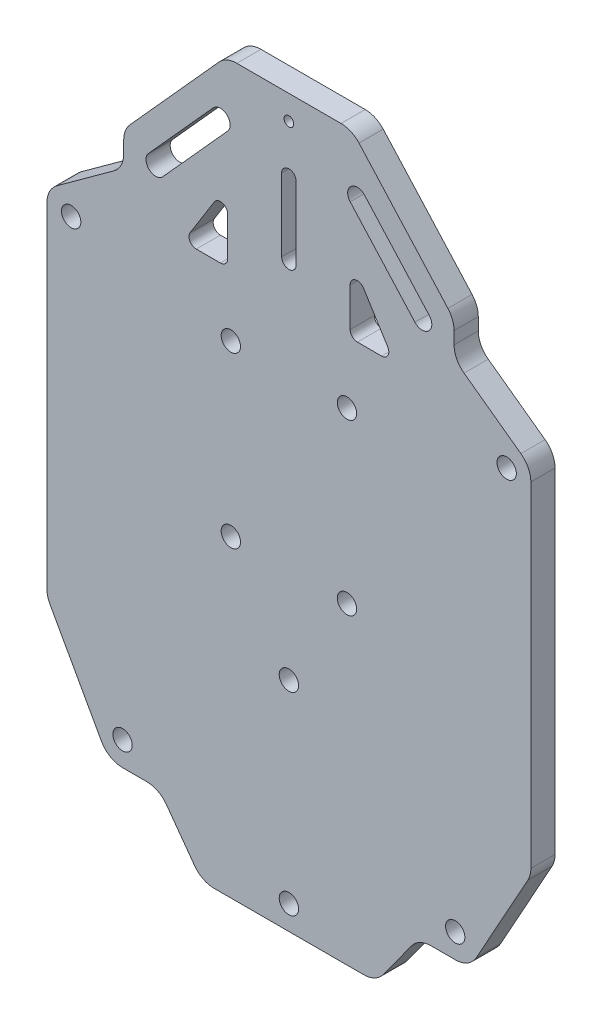
SolidWorks part; units mm, degrees
material "Acrylic (Medium-high impact)"
ref_plane "Front Plane" through (0, 0, 0) normal (0, 0, 1) x (1, 0, 0)
ref_plane "Top Plane" through (0, 0, 0) normal (0, 1, 0) x (1, 0, 0)
ref_plane "Right Plane" through (0, 0, 0) normal (1, 0, 0) x (0, 0, -1)
sketch "Sketch2" plane through (0, 0, 0) normal (0, 0, 1) x (1, 0, 0)
  line L0 (0, 0) -> (0, -150) construction
  line L1 (10.7739, 0) -> (-10.7739, 0)
  line L2 (-14.4896, -1.6543) -> (-32.8523, -22.0482)
  line L3 (-34.1366, -25.3939) -> (-34.1366, -27.9269)
  line L4 (-36.1977, -31.972) -> (-47.9389, -40.5025)
  line L5 (-50, -44.5476) -> (-50, -113.7061)
  line L6 (-19.4975, -147.9389) -> (-25.3193, -139.9258)
  line L7 (-29.3644, -137.8647) -> (-34.3726, -137.8647)
  line L8 (-38.7449, -135.2901) -> (-49.3724, -116.1315)
  line L9 (-15.4524, -150) -> (15.4524, -150)
  line L10 (19.4975, -147.9389) -> (25.3193, -139.9258)
  line L11 (29.3644, -137.8647) -> (34.3726, -137.8647)
  line L12 (38.7449, -135.2901) -> (49.3724, -116.1315)
  line L13 (50, -44.5476) -> (50, -113.7061)
  line L14 (36.1977, -31.972) -> (47.9389, -40.5025)
  line L15 (34.1366, -25.3939) -> (34.1366, -27.9269)
  line L16 (14.4896, -1.6543) -> (32.8523, -22.0482)
  line L17 (-14.147, -11.7352) -> (-27.5296, -26.5981) construction
  line L18 (-12.6607, -13.0735) -> (-26.0433, -27.9364)
  line L19 (-15.6333, -10.397) -> (-29.0159, -25.2599)
  line L20 (14.147, -37.4364) -> (19.147, -37.4364)
  line L21 (-14.147, -37.4364) -> (-19.147, -37.4364)
  line L22 (-12.647, -27.9364) -> (-12.647, -35.9364)
  line L24 (20.419, -35.1414) -> (15.419, -27.1414)
  line L26 (-20.419, -35.1414) -> (-15.419, -27.1414)
  line L27 (12.647, -27.9364) -> (12.647, -35.9364)
  line L28 (14.147, -11.7352) -> (27.5296, -26.5981) construction
  line L29 (12.6607, -13.0735) -> (26.0433, -27.9364)
  line L30 (15.6333, -10.397) -> (29.0159, -25.2599)
  line L31 (0, -15) -> (0, -30) construction
  line L32 (1.5, -15) -> (1.5, -30)
  line L33 (-1.5, -15) -> (-1.5, -30)
  line L34 (0, -50.308) -> (-12, -50.308) construction
  line L35 (14.147, -123.5201) -> (-14.147, -123.5201) construction
  arc A0 (-50, -113.7061) -> (-49.3724, -116.1315) centre (-45, -113.7061) ccw
  arc A1 (-19.4975, -147.9389) -> (-15.4524, -150) centre (-15.4524, -145) ccw
  arc A2 (-25.3193, -139.9258) -> (-29.3644, -137.8647) centre (-29.3644, -142.8647) ccw
  arc A3 (-34.3726, -137.8647) -> (-38.7449, -135.2901) centre (-34.3726, -132.8647) cw
  arc A4 (-47.9389, -40.5025) -> (-50, -44.5476) centre (-45, -44.5476) ccw
  arc A5 (-34.1366, -27.9269) -> (-36.1977, -31.972) centre (-39.1366, -27.9269) cw
  arc A6 (-32.8523, -22.0482) -> (-34.1366, -25.3939) centre (-29.1366, -25.3939) ccw
  arc A7 (-10.7739, 0) -> (-14.4896, -1.6543) centre (-10.7739, -5) ccw
  arc A8 (19.4975, -147.9389) -> (15.4524, -150) centre (15.4524, -145) cw
  arc A9 (25.3193, -139.9258) -> (29.3644, -137.8647) centre (29.3644, -142.8647) cw
  arc A10 (34.3726, -137.8647) -> (38.7449, -135.2901) centre (34.3726, -132.8647) ccw
  arc A11 (50, -113.7061) -> (49.3724, -116.1315) centre (45, -113.7061) cw
  arc A12 (47.9389, -40.5025) -> (50, -44.5476) centre (45, -44.5476) cw
  arc A13 (34.1366, -27.9269) -> (36.1977, -31.972) centre (39.1366, -27.9269) ccw
  arc A14 (32.8523, -22.0482) -> (34.1366, -25.3939) centre (29.1366, -25.3939) cw
  arc A15 (10.7739, 0) -> (14.4896, -1.6543) centre (10.7739, -5) cw
  arc A16 (-12.6607, -13.0735) -> (-15.6333, -10.397) centre (-14.147, -11.7352) ccw
  arc A17 (-29.0159, -25.2599) -> (-26.0433, -27.9364) centre (-27.5296, -26.5981) ccw
  circle A18 centre (0, -5) radius 1
  arc A19 (-12.647, -27.9364) -> (-15.419, -27.1414) centre (-14.147, -27.9364) ccw
  arc A20 (-14.147, -37.4364) -> (-12.647, -35.9364) centre (-14.147, -35.9364) ccw
  arc A21 (-14.147, -37.4364) -> (-12.647, -35.9364) centre (-14.147, -35.9364) ccw
  arc A22 (-20.419, -35.1414) -> (-19.147, -37.4364) centre (-19.147, -35.9364) ccw
  arc A23 (20.419, -35.1414) -> (19.147, -37.4364) centre (19.147, -35.9364) cw
  arc A24 (12.647, -27.9364) -> (15.419, -27.1414) centre (14.147, -27.9364) cw
  arc A25 (14.147, -37.4364) -> (12.647, -35.9364) centre (14.147, -35.9364) cw
  arc A26 (12.6607, -13.0735) -> (15.6333, -10.397) centre (14.147, -11.7352) cw
  arc A27 (29.0159, -25.2599) -> (26.0433, -27.9364) centre (27.5296, -26.5981) cw
  arc A28 (1.5, -15) -> (-1.5, -15) centre (0, -15) ccw
  arc A29 (-1.5, -30) -> (1.5, -30) centre (0, -30) ccw
  circle A30 centre (0, -145) radius 2
  circle A31 centre (0, -105) radius 2
  circle A32 centre (-12, -50.308) radius 2
  circle A33 centre (12, -50.308) radius 2
  circle A34 centre (12, -85.308) radius 2
  circle A35 centre (-12, -85.308) radius 2
  circle A36 centre (-34.3726, -132.8647) radius 2
  circle A37 centre (34.3726, -132.8647) radius 2
  circle A38 centre (-45, -44.5476) radius 2
  circle A39 centre (45, -44.5476) radius 2
  text T0 "OCOBOT" font "Exotc350 Bd BT" height 4
  point P13 (-50, -115)
  point P16 (-18, -150)
  point P19 (-26.8168, -137.8647)
  point P22 (-37.3168, -137.8647)
  point P25 (-50, -42)
  point P28 (-34.1366, -30.4746)
  point P31 (-34.1366, -23.4746)
  point P34 (-13, 0)
  point P56 (34.1366, -23.4746)
  point P62 (-20.8383, -19.1667)
  point P71 (-18.0805, -35.9364)
  point P73 (-14.147, -31.9364)
  point P76 (0, -22.5)
  point P100 (20.8383, -19.1667)
  point P111 (0, -75)
  point P125 (0, -123.5201)
  dimension "D10" = 5
  dimension "D13" = 5
  dimension "D14" = 5
  dimension "D16" = 2
  dimension "D19" = 2
  dimension "D20" = 5
  dimension "D24" = 1.5
  dimension "D25" = 1.5
  dimension "D26" = 1.5
  dimension "D34" = 1.5
  dimension "D37" = 4
  dimension "D38" = 4
  dimension "D40" = 4
  dimension "D47" = 4
  dimension "D48" = 4
  dimension "D49" = 5
  dimension "D50" = 4
  dimension "D51" = 4
  dimension "D52" = 4
  dimension "D53" = 4
  dimension "D1" = 150
  dimension "D2" = 100
  dimension "D3" = 73
  dimension "D4" = 36
  dimension "D5" = 15
  dimension "D6" = 26
  dimension "D7" = 35
  dimension "D8" = 10.5
  dimension "D9" = 54
  dimension "D11" = 48
  dimension "D12" = 7
  dimension "D15" = 5
  dimension "D17" = 14.147
  dimension "D18" = 20
  dimension "D21" = 8
  dimension "D22" = 5
  dimension "D23" = 14.147
  dimension "D27" = 19.478
  dimension "D28" = 112.5636
  dimension "D29" = 31.9364
  dimension "D30" = 27.9364
  dimension "D31" = 14.147
  dimension "D32" = 18.0805
  dimension "D33" = 35.9364
  dimension "D35" = 15
  dimension "D36" = 15
  dimension "D39" = 40
  dimension "D41" = 12
  dimension "D42" = 50.308
  dimension "D43" = 35
  dimension "D44" = 24
  dimension "D45" = 35
  dimension "D46" = 35
extrude "Boss-Extrude1" add sketch "Sketch2" along normal blind 5 contours A15 L1 A7 L2 A6 L3 A5 L4 A4 L5 A0 L8 A3 L7 A2 L6 A1 L9 A8 L10 A9 L11 A10 L12 A11 L13 A12 L14 A13 L15 A14 L16 A39 A38 A37 A36 A33 A32 A31 A30 A29 L33
